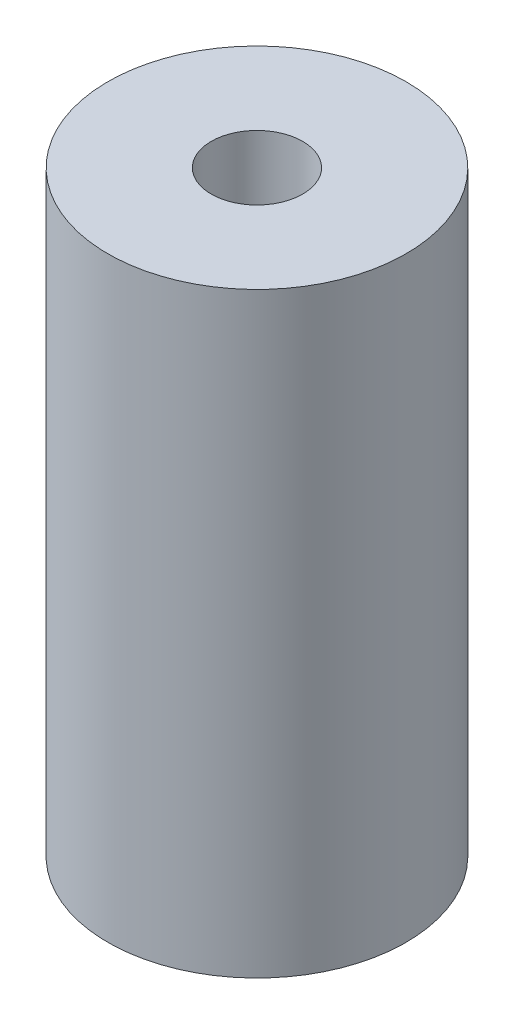
SolidWorks part; units mm, degrees
ref_plane "Front Plane" through (0, 0, 0) normal (0, 0, 1) x (1, 0, 0)
ref_plane "Top Plane" through (0, 0, 0) normal (0, 1, 0) x (1, 0, 0)
ref_plane "Right Plane" through (0, 0, 0) normal (1, 0, 0) x (0, 0, -1)
sketch "Sketch1" plane through (0, 0, 0) normal (0, 1, 0) x (1, 0, 0)
  circle A0 centre (0, 0) radius 1.4605
  circle A1 centre (0, 0) radius 4.7625
  dimension "D1" = 2.921
extrude "Boss-Extrude1" add sketch "Sketch1" along normal blind 19.05
